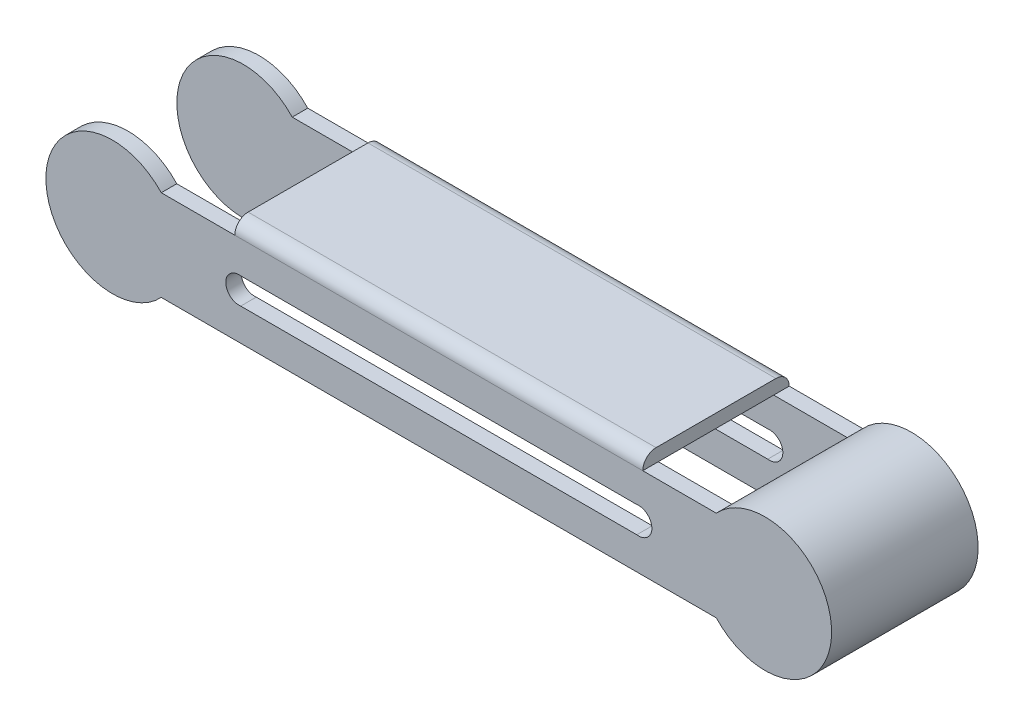
SolidWorks part; units mm, degrees
material "6061 Alloy"
ref_plane "Front Plane" through (0, 0, 0) normal (0, 0, 1) x (1, 0, 0)
ref_plane "Top Plane" through (0, 0, 0) normal (0, 1, 0) x (1, 0, 0)
ref_plane "Right Plane" through (0, 0, 0) normal (1, 0, 0) x (0, 0, -1)
sketch "Sketch1" plane through (0, 0, 0) normal (0, 0, 1) x (1, 0, 0)
  line L0 (-73.5, 0) -> (73.5, 0) construction
  line L2 (-62.5129, 10.2119) -> (62.5129, 10.2119)
  line L4 (-62.5129, -10.2119) -> (62.5129, -10.2119)
  line L6 (-62.5129, 10.2119) -> (62.5129, -10.2119) construction
  line L7 (-62.5129, -10.2119) -> (62.5129, 10.2119) construction
  arc A0 (-62.5129, 10.2119) -> (-62.5129, -10.2119) centre (-73.5, 0) ccw
  arc A1 (62.5129, -10.2119) -> (62.5129, 10.2119) centre (73.5, 0) ccw
  point P5 (0, 0)
  dimension "D1" = 15
  dimension "D2" = 15
  dimension "D3" = 147
  dimension "D4" = 10.2119
extrude "Boss-Extrude1" add sketch "Sketch1" along normal blind 33
ref_plane "Plane1" through (0, 0, 43) normal (0, 0, 1) x (1, 0, 0)
sketch "Sketch2" plane through (0, 0, 43) normal (0, 0, 1) x (1, 0, 0)
  line L0 (-45, 0) -> (45.0279, 0) construction
  line L2 (44.6061, 2.95) -> (-44.6061, 2.95)
  line L4 (44.6061, -2.95) -> (-44.6061, -2.95)
  line L6 (44.6061, 2.95) -> (-44.6061, -2.95) construction
  line L7 (44.6061, -2.95) -> (-44.6061, 2.95) construction
  arc A0 (-44.6061, 2.95) -> (-44.6061, -2.95) centre (-45, 0) ccw
  arc A1 (44.6061, -2.95) -> (44.6061, 2.95) centre (45.0279, 0) ccw
  point P5 (0, 0)
  dimension "D1" = 2.9762
  dimension "D2" = 2.98
  dimension "D4" = 45
  dimension "D3" = 5.9
extrude "Cut-Extrude1" cut sketch "Sketch2" against normal blind 60
sketch "Sketch3" plane through (0, 10.2119, 0) normal (0, 1, 0) x (1, 0, 0)
  line L0 (-62.5129, -16.5) -> (62.5129, -16.5) construction
  line L1 (-62.5129, -33) -> (-62.5129, 0) construction
  line L2 (62.5129, -33) -> (62.5129, 0) construction
  line L3 (0, 0) -> (0, -33) construction
  line L4 (62.5129, 0) -> (-62.5129, 0) construction
  line L5 (62.5129, -33) -> (-62.5129, -33) construction
  line L7 (-62.5129, -3.5) -> (62.5129, -3.5)
  line L8 (-62.5129, -3.5) -> (-62.5129, -29.5)
  line L9 (-62.5129, -29.5) -> (62.5129, -29.5)
  line L10 (62.5129, -3.5) -> (62.5129, -29.5)
  line L11 (-62.5129, -3.5) -> (62.5129, -29.5) construction
  line L12 (-62.5129, -29.5) -> (62.5129, -3.5) construction
  point P13 (0, -16.5)
  dimension "D1" = 26
extrude "Cut-Extrude2" cut sketch "Sketch3" against normal blind 25
ref_plane "Plane2" through (0, 10.2119, 0) normal (0, -1, 0) x (-1, 0, 0)
sketch "Sketch7" plane through (0, 10.2119, 0) normal (0, -1, 0) x (-1, 0, 0)
  line L0 (0, 0) -> (0, -33) construction
  line L1 (-62.5129, 0) -> (62.5129, 0) construction
  line L2 (-62.5129, -33) -> (62.5129, -33) construction
  line L3 (112.5129, -16.5) -> (62.5129, -16.5) construction
  line L4 (62.5129, -3.5) -> (62.5129, -29.5) construction
  line L6 (112.5129, -3.5) -> (62.5129, -3.5)
  line L7 (112.5129, -3.5) -> (112.5129, -29.5)
  line L8 (112.5129, -29.5) -> (62.5129, -29.5)
  line L9 (62.5129, -3.5) -> (62.5129, -29.5)
  line L10 (112.5129, -3.5) -> (62.5129, -29.5) construction
  line L11 (112.5129, -29.5) -> (62.5129, -3.5) construction
  point P10 (87.5129, -16.5)
  dimension "D1" = 50
  dimension "D2" = 26
extrude "Cut-Extrude6" cut sketch "Sketch7" against normal through all both and the other way through all
sketch "Sketch8" plane through (0, 10.2119, 0) normal (0, 1, 0) x (1, 0, 0)
  line L0 (0, 0) -> (0, -33) construction
  line L1 (62.5129, -33) -> (-62.5129, -33) construction
  line L3 (-45.9494, 0) -> (45.9494, 0)
  line L4 (-45.9494, 0) -> (-45.9494, -33)
  line L5 (-45.9494, -33) -> (45.9494, -33)
  line L6 (45.9494, 0) -> (45.9494, -33)
  line L7 (-45.9494, 0) -> (45.9494, -33) construction
  line L8 (-45.9494, -33) -> (45.9494, 0) construction
  point P5 (0, -16.5)
extrude "Boss-Extrude2" add sketch "Sketch8" along normal blind 3
sketch "Sketch9" plane through (0, 0, 33) normal (0, 0, 1) x (1, 0, 0)
  line L0 (-45.9494, 10.2119) -> (45.9494, 10.2119)
split line "Split Line1"
sketch "Sketch10" plane through (0, 0, 0) normal (0, 0, -1) x (-1, 0, 0)
  line L0 (-45.9494, 10.2119) -> (45.9494, 10.2119)
split line "Split Line2"
fillet "Fillet1" radius 3 2 edges at (0, 13.2119, 0) (0, 13.2119, 33)
